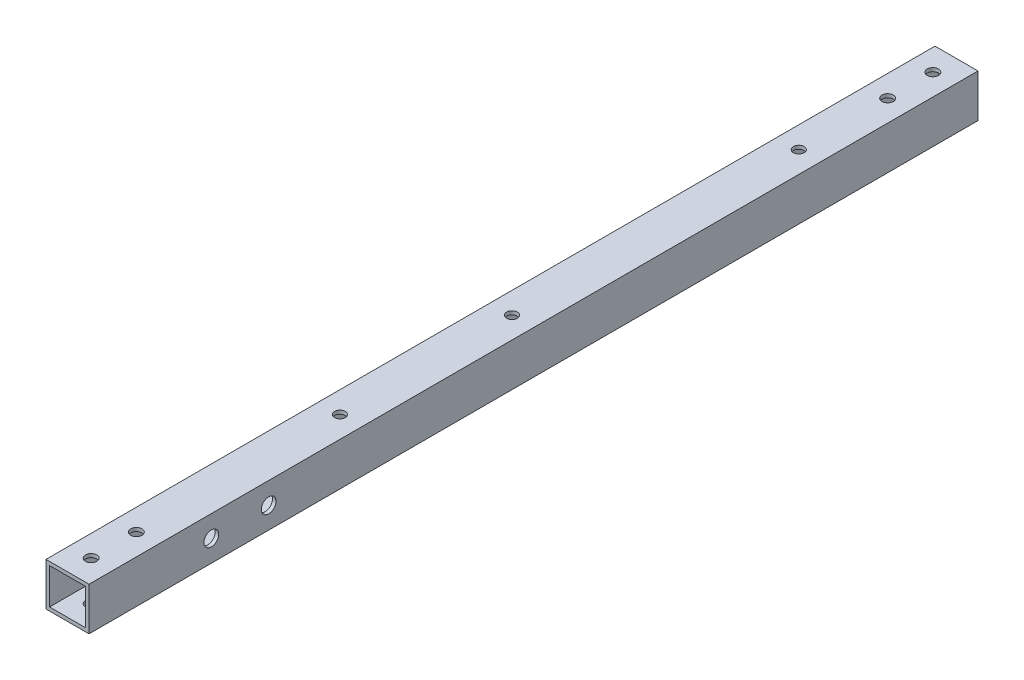
SolidWorks part; units mm, degrees
material "6061 Alloy"
ref_plane "Front Plane" through (0, 0, 0) normal (0, 0, 1) x (1, 0, 0)
ref_plane "Top Plane" through (0, 0, 0) normal (0, 1, 0) x (1, 0, 0)
ref_plane "Right Plane" through (0, 0, 0) normal (1, 0, 0) x (0, 0, -1)
sketch "Sketch1" plane through (0, 0, 0) normal (0, 0, 1) x (1, 0, 0)
  line L1 (-7.9375, -7.9375) -> (7.9375, -7.9375)
  line L2 (-7.9375, -7.9375) -> (-7.9375, 7.9375)
  line L3 (-7.9375, 7.9375) -> (7.9375, 7.9375)
  line L4 (7.9375, -7.9375) -> (7.9375, 7.9375)
  line L5 (-7.9375, -7.9375) -> (7.9375, 7.9375) construction
  line L6 (-7.9375, 7.9375) -> (7.9375, -7.9375) construction
  line L7 (-9.525, -9.525) -> (9.525, -9.525)
  line L8 (-9.525, -9.525) -> (-9.525, 9.525)
  line L9 (-9.525, 9.525) -> (9.525, 9.525)
  line L10 (9.525, -9.525) -> (9.525, 9.525)
  line L11 (-9.525, -9.525) -> (9.525, 9.525) construction
  line L12 (-9.525, 9.525) -> (9.525, -9.525) construction
  point P0 (0, 0)
  point P6 (0, 0)
  dimension "D1" = 19.05
  dimension "D2" = 19.05
  dimension "D3" = 1.5875
  dimension "D4" = 1.5875
extrude "Boss-Extrude1" add sketch "Sketch1" along normal mid plane 393.7
extrude "Cut-Extrude1" cut sketch "Sketch2" against normal blind 30
sketch "Sketch2" plane through (0, 13.525, 0) normal (0, 1, 0) x (1, 0, 0)
  circle A0 centre (0, -206.375) radius 2.5
  circle A1 centre (0, -186.375) radius 2.5
  circle A2 centre (0, -166.375) radius 2.5
  circle A3 centre (20, -206.375) radius 2.5
  circle A4 centre (40, -206.375) radius 2.5
mirror "Mirror1" of "Cut-Extrude1"
extrude "Cut-Extrude2" cut sketch "Sketch3" against normal blind 30
sketch "Sketch3" plane through (-14.3002, 0, 0) normal (-1, 0, 0) x (0, 0, 1)
  circle A0 centre (142.675, 0) radius 3.2639
  circle A1 centre (117.275, 0) radius 3.2639
extrude "Cut-Extrude3" cut sketch "Sketch4" against normal blind 30
sketch "Sketch4" plane through (0, 18.1864, 0) normal (0, 1, 0) x (1, 0, 0)
  circle A0 centre (0, 0) radius 2.3813
  circle A1 centre (152.4, -127) radius 2.3813
  circle A2 centre (152.4, 127) radius 2.3813
  circle A3 centre (152.4, -50.8) radius 2.3812
  circle A4 centre (152.4, 50.8) radius 2.3813
  circle A5 centre (0, 127) radius 2.3813
  circle A6 centre (0, -76.2) radius 2.3813
  circle A7 centre (-152.4, -127) radius 2.3813
  circle A8 centre (-152.4, 127) radius 2.3813
  circle A9 centre (-152.4, 50.8) radius 2.3813
  circle A10 centre (-152.4, -50.8) radius 2.3813
